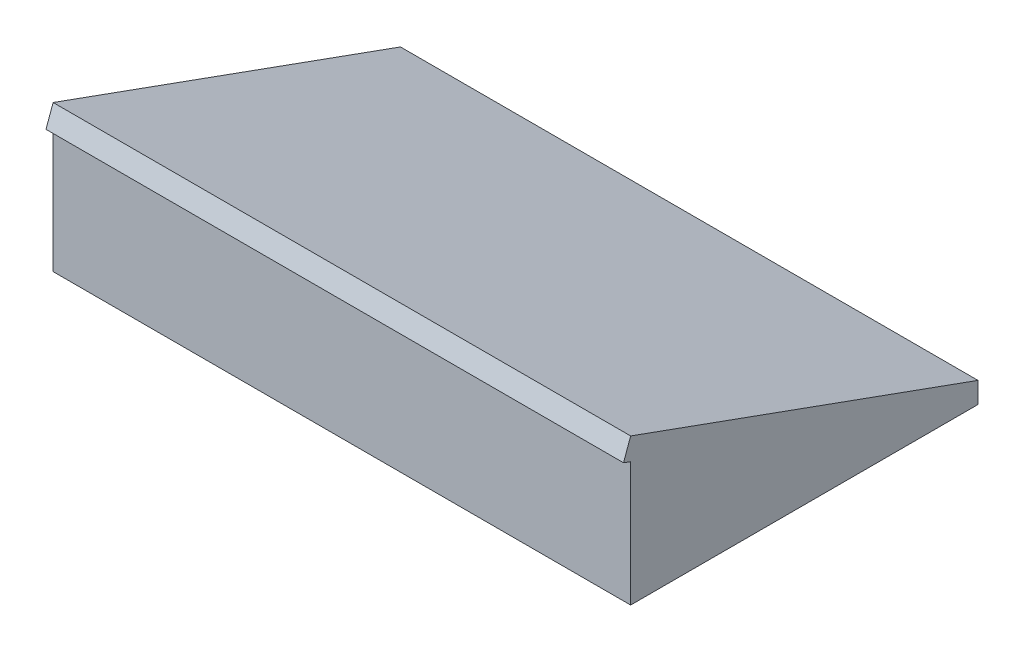
SolidWorks part; units mm, degrees
ref_plane "Ebene vorne" through (0, 0, 0) normal (0, 0, 1) x (1, 0, 0)
ref_plane "Ebene oben" through (0, 0, 0) normal (0, 1, 0) x (1, 0, 0)
ref_plane "Ebene rechts" through (0, 0, 0) normal (1, 0, 0) x (0, 0, -1)
sketch "Sketch1" plane through (0, 0, 0) normal (0, 1, 0) x (1, 0, 0)
  line L1 (-69, -41.5) -> (69, -41.5)
  line L2 (-69, -41.5) -> (-69, 41.5)
  line L3 (-69, 41.5) -> (69, 41.5)
  line L4 (69, -41.5) -> (69, 41.5)
  line L5 (-69, -41.5) -> (69, 41.5) construction
  line L6 (-69, 41.5) -> (69, -41.5) construction
  point P0 (0, 0)
  dimension "D1" = 138
  dimension "D2" = 83
extrude "Boss-Extrude1" add sketch "Sketch1" along normal blind 5
ref_plane "Plane2" through (69, 0, 0) normal (1, 0, 0) x (0, 0, -1)
sketch "Sketch2" plane through (69, 0, 0) normal (1, 0, 0) x (0, 0, -1)
  line L0 (-41.5, 5) -> (-41.5, 35)
  line L1 (-41.5, 35) -> (41.5, 5)
  line L2 (41.5, 5) -> (-41.5, 5)
  dimension "D1" = 30
extrude "Boss-Extrude2" add sketch "Sketch2" against normal blind 5 separate body
ref_plane "Plane3" through (-69, 0, 0) normal (-1, 0, 0) x (0, 0, 1)
sketch "Sketch4" plane through (-69, 0, 0) normal (-1, 0, 0) x (0, 0, 1)
  line L0 (41.5, 5) -> (41.5, 35)
  line L1 (41.5, 35) -> (-41.5, 5)
  line L2 (41.5, 5) -> (-41.5, 5)
  dimension "D1" = 30
extrude "Boss-Extrude3" add sketch "Sketch4" against normal blind 5
sketch "Sketch5" plane through (0, 0, 41.5) normal (0, 0, 1) x (1, 0, 0)
  line L1 (-64, 5) -> (64, 5)
  line L2 (-64, 5) -> (-64, 30)
  line L3 (-64, 30) -> (64, 30)
  line L4 (64, 5) -> (64, 30)
  dimension "D1" = 25
extrude "Boss-Extrude4" add sketch "Sketch5" against normal blind 5
ref_plane "Plane4" through (0, 17.689, -6.3936) normal (0, 0.9405, -0.3399) x (1, 0, 0)
sketch "Sketch7" plane through (0, 17.689, -6.3936) normal (0, 0.9405, -0.3399) x (1, 0, 0)
  line L1 (69, -50.9261) -> (-69, -50.9261)
  line L2 (69, -50.9261) -> (69, 37.3292)
  line L3 (69, 37.3292) -> (-69, 37.3292)
  line L4 (-69, -50.9261) -> (-69, 37.3292)
extrude "Boss-Extrude7" add sketch "Sketch7" against normal blind 5
